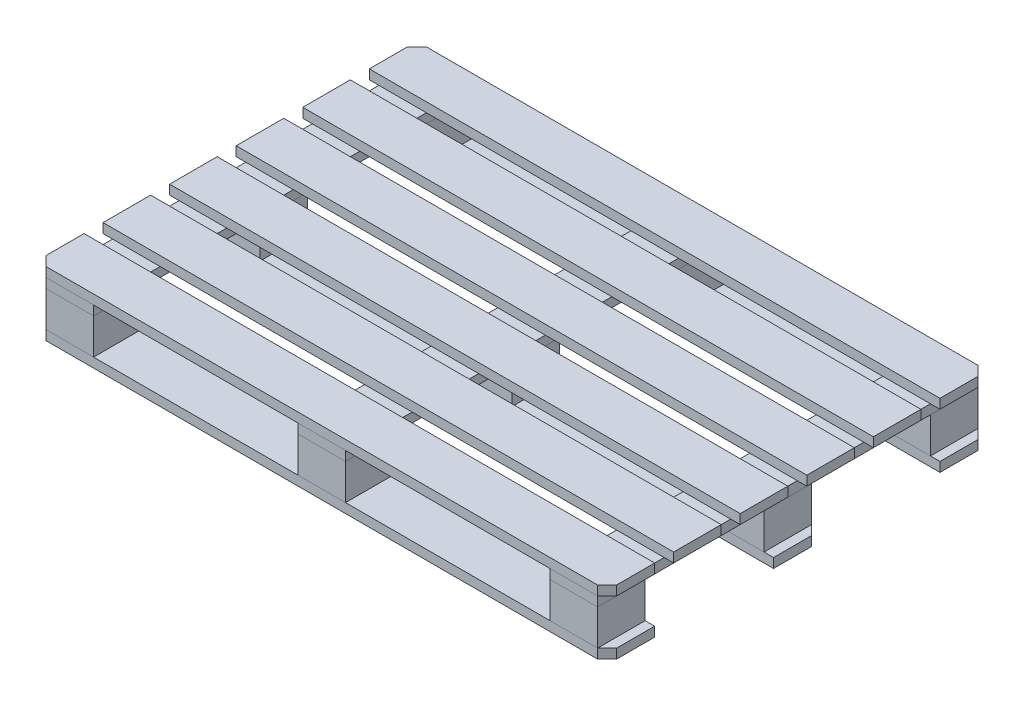
SolidWorks part; units mm, degrees
material "Chêne"
ref_plane "Plan de face" through (0, 0, 0) normal (0, 0, 1) x (1, 0, 0)
ref_plane "Plan de dessus" through (0, 0, 0) normal (0, 1, 0) x (1, 0, 0)
ref_plane "Plan de droite" through (0, 0, 0) normal (1, 0, 0) x (0, 0, -1)
sketch "Esquisse1" plane through (0, 0, 0) normal (0, 1, 0) x (1, 0, 0)
  line L0 (0, 0) -> (-942.0135, 0) construction
  line L1 (600, -400) -> (-600, -400) construction
  line L2 (600, -400) -> (600, 400) construction
  line L3 (600, 400) -> (-600, 400) construction
  line L4 (-600, -400) -> (-600, 400) construction
  line L5 (600, -400) -> (-600, 400) construction
  line L6 (600, 400) -> (-600, -400) construction
  line L7 (-600, 400) -> (600, 400)
  line L8 (-600, 400) -> (-600, 300)
  line L9 (-600, 300) -> (600, 300)
  line L10 (600, 400) -> (600, 300)
  line L11 (-600, 260) -> (600, 260)
  line L12 (-600, 260) -> (-600, 160)
  line L13 (-600, 160) -> (600, 160)
  line L14 (600, 260) -> (600, 160)
  line L15 (-600, 120) -> (600, 120)
  line L16 (-600, 120) -> (-600, 20)
  line L17 (-600, 20) -> (600, 20)
  line L18 (600, 120) -> (600, 20)
  line L19 (600, -400) -> (-600, -400) construction
  line L20 (600, -120) -> (600, -20)
  line L21 (-600, -20) -> (600, -20)
  line L22 (-600, -120) -> (-600, -20)
  line L23 (-600, -120) -> (600, -120)
  line L24 (600, -260) -> (600, -160)
  line L25 (-600, -160) -> (600, -160)
  line L26 (-600, -260) -> (-600, -160)
  line L27 (-600, -260) -> (600, -260)
  line L28 (600, -400) -> (600, -300)
  line L29 (-600, -300) -> (600, -300)
  line L30 (-600, -400) -> (-600, -300)
  line L31 (-600, -400) -> (600, -400)
  point P0 (0, 0)
  dimension "D1" = 1200
  dimension "D2" = 800
  dimension "D3" = 100
  dimension "D4" = 100
  dimension "D5" = 40
  dimension "D6" = 40
  dimension "D7" = 100
extrude "Boss.-Extru.1" add sketch "Esquisse1" along normal blind 20
chamfer "Chanfrein1" distance 20 angle 45 2 edges at (600, 10, 400) (-600, 10, 400)
chamfer "Chanfrein2" distance 20 angle 45 2 edges at (-600, 10, -400) (600, 10, -400)
sketch "Esquisse2" plane through (0, 0, 0) normal (0, 1, 0) x (1, 0, 0)
  line L0 (-580, -400) -> (580, -400) construction
  line L1 (-580, 400) -> (-480, 400)
  line L2 (-580, 400) -> (-580, -400)
  line L3 (-580, -400) -> (-480, -400)
  line L4 (-480, 400) -> (-480, -400)
  line L5 (0, 0) -> (0, -917.183) construction
  line L6 (50, 400) -> (-50, 400)
  line L7 (50, 400) -> (50, -400)
  line L8 (50, -400) -> (-50, -400)
  line L9 (-50, 400) -> (-50, -400)
  line L10 (50, 400) -> (-50, -400) construction
  line L11 (50, -400) -> (-50, 400) construction
  line L12 (480, 400) -> (480, -400)
  line L13 (580, -400) -> (480, -400)
  line L14 (580, 400) -> (580, -400)
  line L15 (580, 400) -> (480, 400)
  point P7 (0, 0)
  dimension "D1" = 100
  dimension "D2" = 100
extrude "Boss.-Extru.2" add sketch "Esquisse2" against normal blind 20 separate body
sketch "Esquisse3" plane through (0, -20, 0) normal (0, -1, 0) x (1, 0, 0)
  line L0 (-480, 400) -> (-480, -400) construction
  line L1 (-580, 400) -> (-480, 400)
  line L2 (-580, 400) -> (-580, 300)
  line L3 (-580, 300) -> (-480, 300)
  line L4 (-480, 400) -> (-480, 300)
  line L5 (50, 400) -> (50, -400) construction
  line L6 (-50, 400) -> (50, 400)
  line L7 (-50, 400) -> (-50, 300)
  line L8 (-50, 300) -> (50, 300)
  line L9 (50, 400) -> (50, 300)
  line L10 (580, 400) -> (580, -400) construction
  line L11 (480, 400) -> (580, 400)
  line L12 (480, 400) -> (480, 300)
  line L13 (480, 300) -> (580, 300)
  line L14 (580, 400) -> (580, 300)
  line L15 (0, 0) -> (-927.9626, 0) construction
  line L16 (580, -400) -> (580, -300)
  line L17 (480, -300) -> (580, -300)
  line L18 (480, -400) -> (480, -300)
  line L19 (480, -400) -> (580, -400)
  line L20 (50, -400) -> (50, -300)
  line L21 (-50, -300) -> (50, -300)
  line L22 (-50, -400) -> (-50, -300)
  line L23 (-50, -400) -> (50, -400)
  line L24 (-480, -400) -> (-480, -300)
  line L25 (-580, -300) -> (-480, -300)
  line L26 (-580, -400) -> (-580, -300)
  line L27 (-580, -400) -> (-480, -400)
  line L28 (-480, 350) -> (-480, -350) construction
  line L29 (-580, -50) -> (-480, -50)
  line L30 (480, -50) -> (480, 50)
  line L31 (-50, -50) -> (50, -50)
  line L32 (480, -50) -> (580, -50)
  line L33 (-480, -50) -> (-480, 50)
  line L34 (-580, -50) -> (-580, 50)
  line L35 (580, -50) -> (580, 50)
  line L36 (-50, 50) -> (50, 50)
  line L37 (-50, -50) -> (-50, 50)
  line L38 (50, -50) -> (50, 50)
  line L39 (-580, 50) -> (-480, 50)
  line L40 (480, 50) -> (580, 50)
  dimension "D1" = 100
  dimension "D2" = 100
  dimension "D3" = 100
extrude "Boss.-Extru.3" add sketch "Esquisse3" along normal blind 75 separate body
sketch "Esquisse4" plane through (0, -95, 0) normal (0, -1, 0) x (1, 0, 0)
  line L0 (0, 0) -> (-1187.223, 0) construction
  line L1 (580, 400) -> (-580, 400)
  line L2 (600, 380) -> (600, 300)
  line L3 (600, 300) -> (-600, 300)
  line L4 (-600, 380) -> (-600, 300)
  line L5 (600, 400) -> (-600, 300) construction
  line L6 (600, 300) -> (-600, 400) construction
  line L7 (-580, 400) -> (-600, 380)
  line L8 (600, 380) -> (580, 400)
  line L9 (-600, 300) -> (-600, 380) construction
  line L10 (600, -300) -> (-600, -400) construction
  line L11 (600, -400) -> (-600, -300) construction
  line L12 (600, -380) -> (580, -400)
  line L13 (-580, -400) -> (-600, -380)
  line L14 (-600, -380) -> (-600, -300)
  line L15 (600, -300) -> (-600, -300)
  line L16 (600, -380) -> (600, -300)
  line L17 (580, -400) -> (-580, -400)
  line L18 (580, -50) -> (-580, -50)
  line L19 (600, -50) -> (-600, 50) construction
  line L20 (600, -30) -> (600, 50)
  line L21 (600, 50) -> (-600, -50) construction
  line L22 (600, 50) -> (-600, 50)
  line L23 (600, -30) -> (580, -50)
  line L24 (-580, -50) -> (-600, -30)
  line L25 (-600, -30) -> (-600, 50)
  point P0 (0, 350)
  point P22 (0, -350)
  point P31 (0, 0)
  dimension "D1" = 1200
  dimension "D2" = 0
extrude "Boss.-Extru.4" add sketch "Esquisse4" along normal blind 20 separate body
